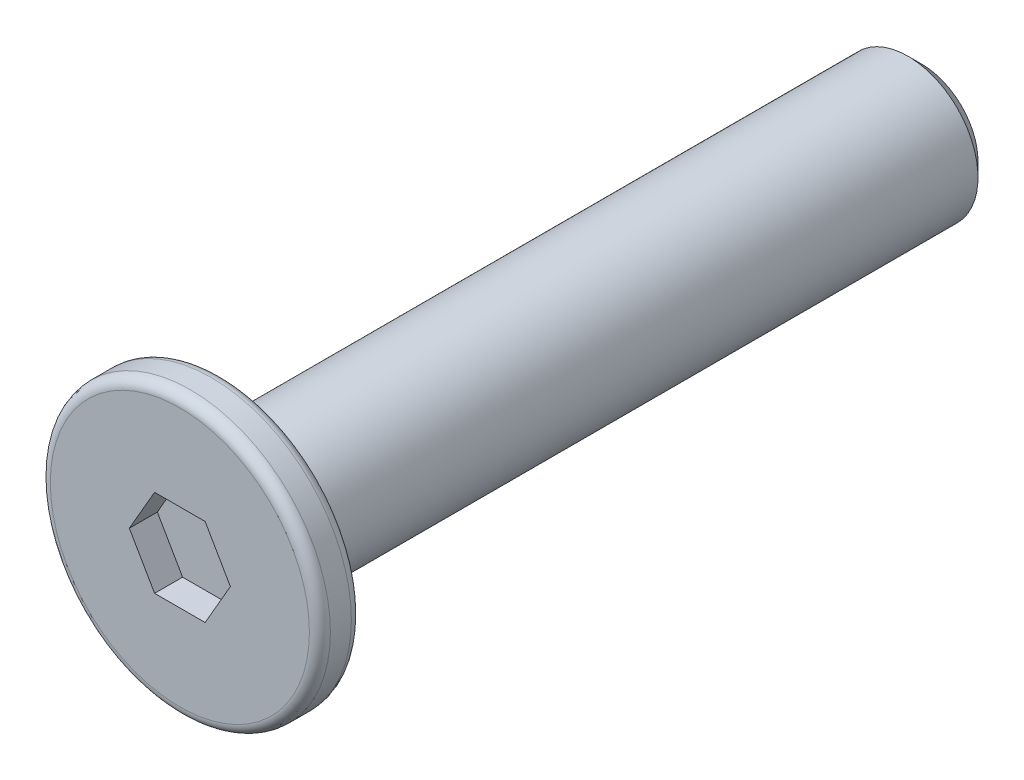
SolidWorks part; units mm, degrees
ref_plane "前视基准面" through (0, 0, 0) normal (0, 0, 1) x (1, 0, 0)
ref_plane "上视基准面" through (0, 0, 0) normal (0, 1, 0) x (1, 0, 0)
ref_plane "右视基准面" through (0, 0, 0) normal (1, 0, 0) x (0, 0, -1)
sketch "草图1" plane through (0, 0, 0) normal (0, 0, 1) x (1, 0, 0)
  circle A0 centre (0, 0) radius 4
  dimension "D1" = 8
extrude "凸台-拉伸1" add sketch "草图1" along normal mid plane 1.2
sketch "草图2" plane through (0, 0, -0.6) normal (0, 0, -1) x (-1, 0, 0)
  circle A0 centre (0, 0) radius 2
  dimension "D1" = 4
extrude "凸台-拉伸2" add sketch "草图2" along normal blind 20
chamfer "倒角1" distance 0.4 angle 45 1 edges at (-2, 0, -20.6)
sketch "草图3" plane through (0, 0, 0.6) normal (0, 0, 1) x (1, 0, 0)
  line L1 (1.4434, 0) -> (0.7217, 1.25)
  line L2 (0.7217, 1.25) -> (-0.7217, 1.25)
  line L3 (-0.7217, 1.25) -> (-1.4434, 0)
  line L4 (-1.4434, 0) -> (-0.7217, -1.25)
  line L5 (-0.7217, -1.25) -> (0.7217, -1.25)
  line L6 (0.7217, -1.25) -> (1.4434, 0)
  circle A0 centre (0, 0) radius 1.25 construction
  dimension "D1" = 2.5
extrude "切除-拉伸1" cut sketch "草图3" against normal blind 0.8
fillet "圆角2" radius 0.3 2 edges at (4, 0, -0.6) (4, 0, 0.6)
